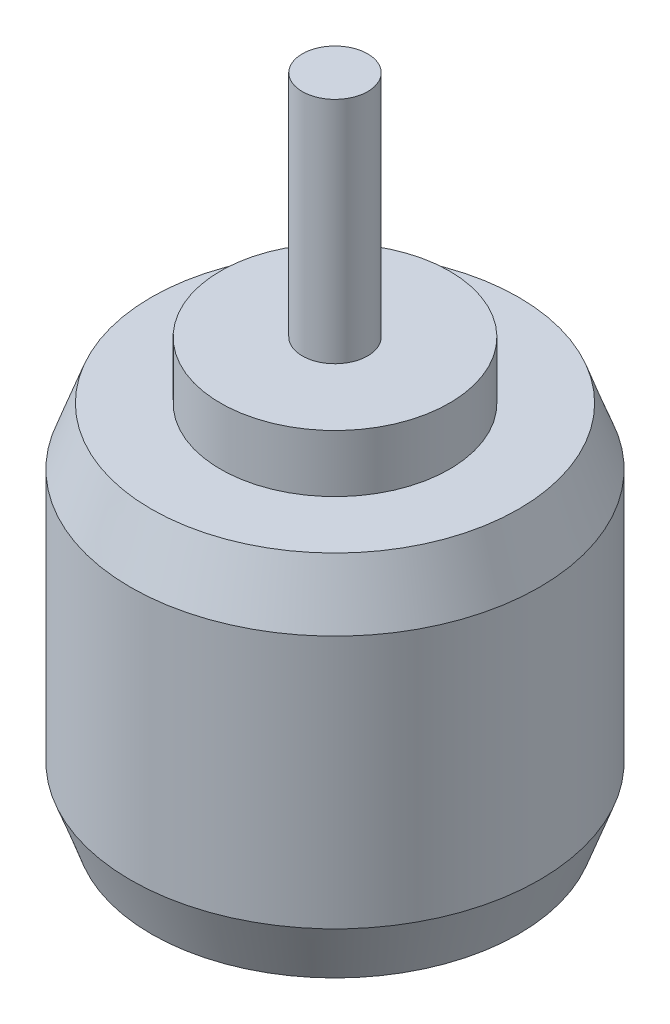
SolidWorks part; units mm, degrees
ref_plane "Front Plane" through (0, 0, 0) normal (0, 0, 1) x (1, 0, 0)
ref_plane "Top Plane" through (0, 0, 0) normal (0, 1, 0) x (1, 0, 0)
ref_plane "Right Plane" through (0, 0, 0) normal (1, 0, 0) x (0, 0, -1)
sketch "Sketch1" plane through (0, 0, 0) normal (0, 0, 1) x (1, 0, 0)
  line L0 (0, 0) -> (25, 0)
  line L1 (25, 0) -> (25, 45)
  line L2 (0, 0) -> (3, 0)
  line L3 (0, 0) -> (0, -2)
  line L4 (0, -2) -> (3, -2)
  line L5 (3, 0) -> (3, -2)
  line L6 (0, 0) -> (0, 45)
  line L7 (25, 45) -> (0, 45)
  line L9 (0, 45) -> (4, 45)
  line L10 (0, 45) -> (0, 80)
  line L11 (0, 80) -> (4, 80)
  line L12 (4, 45) -> (4, 80)
  line L13 (0, 45) -> (14, 45)
  line L14 (0, 45) -> (0, 52)
  line L15 (0, 52) -> (14, 52)
  line L16 (14, 45) -> (14, 52)
  dimension "D1" = 25
  dimension "D2" = 2
  dimension "D3" = 3
  dimension "D4" = 45
  dimension "D5" = 4
  dimension "D6" = 35
  dimension "D7" = 28
  dimension "D8" = 14
revolve "Revolve1" add sketch "Sketch1" angle 360 about L10
chamfer "Chamfer1" distance 7 angle 20 1 edges at (0, 0, -25)
chamfer "Chamfer2" distance 7 angle 20 1 edges at (0, 45, -25)
sketch "Sketch2" plane through (0, 0, 0) normal (0, -1, 0) x (1, 0, 0)
  circle A0 centre (0, 0) radius 10 construction
  circle A1 centre (0, 10) radius 1.75
  circle A2 centre (10, 0) radius 1.75
  circle A3 centre (0, -10) radius 1.75
  circle A4 centre (-10, 0) radius 1.75
  point P14 (0, 0)
  dimension "D1" = 20
  dimension "D2" = 3.5
  dimension "D3" = 4
extrude "Cut-Extrude1" cut sketch "Sketch2" against normal blind 10
sketch "Sketch3" plane through (0, 45, 0) normal (0, 1, 0) x (1, 0, 0)
  circle A0 centre (0, 0) radius 203.2 construction
  dimension "D1" = 406.4
equation "\"D1@Sketch3\"=16in"
